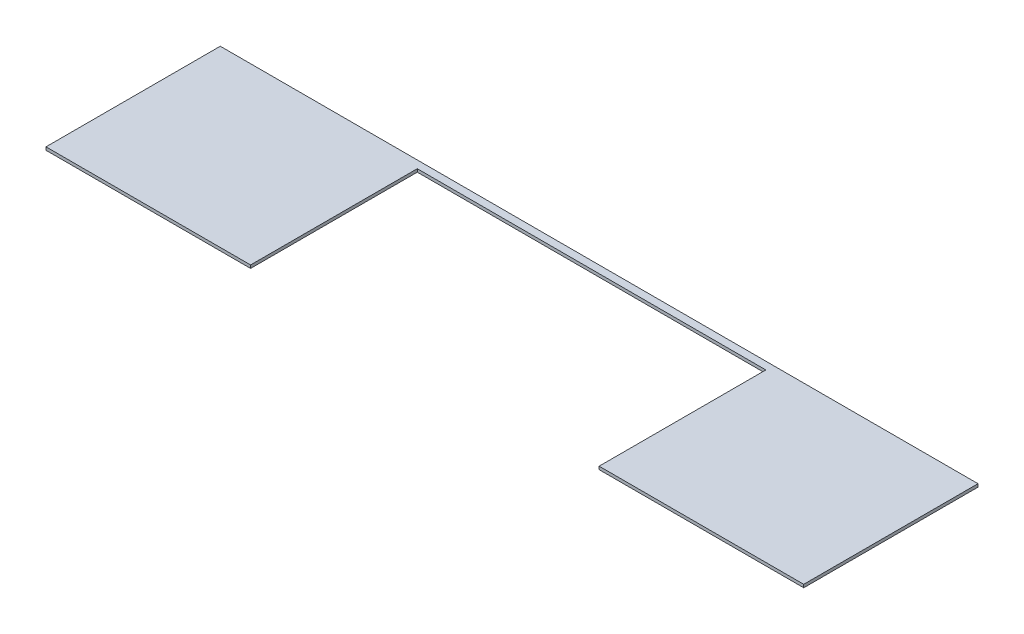
SolidWorks part; units mm, degrees
ref_plane "Front Plane" through (0, 0, 0) normal (0, 0, 1) x (1, 0, 0)
ref_plane "Top Plane" through (0, 0, 0) normal (0, 1, 0) x (1, 0, 0)
ref_plane "Right Plane" through (0, 0, 0) normal (1, 0, 0) x (0, 0, -1)
sketch "Sketch1" plane through (0, 0, 0) normal (0, 1, 0) x (1, 0, 0)
  line L1 (-176.5123, 119.0926) -> (323.4877, 119.0926)
  line L2 (-176.5123, 119.0926) -> (-176.5123, 4.0926)
  line L3 (-176.5123, 4.0926) -> (323.4877, 4.0926)
  line L4 (323.4877, 119.0926) -> (323.4877, 4.0926)
  dimension "D1" = 500
  dimension "D2" = 115
extrude "Boss-Extrude1" add sketch "Sketch1" along normal blind 2
sketch "Sketch2" plane through (0, 2, 0) normal (0, 1, 0) x (1, 0, 0)
  line L0 (-41.5123, 4.0926) -> (-41.5123, 114.0926)
  line L1 (-176.5123, 4.0926) -> (323.4877, 4.0926) construction
  line L2 (-41.5123, 114.0926) -> (188.4877, 114.0926)
  line L3 (188.4877, 114.0926) -> (188.4877, 4.0926)
  line L4 (73.4877, 4.0926) -> (73.4877, 114.0926) construction
  line L6 (-41.5123, 4.0926) -> (188.4877, 4.0926)
  dimension "D1" = 110
  dimension "D2" = 230
extrude "Cut-Extrude1" cut sketch "Sketch2" against normal blind 10
equation "\"clip_tube_diam\"= 6mm"
equation "\"middle_tube_len\"= 500mm"
equation "\"horizontal_pipe_spacing\"= 260mm"
equation "\"belly_plate_width\" = 176mm"
